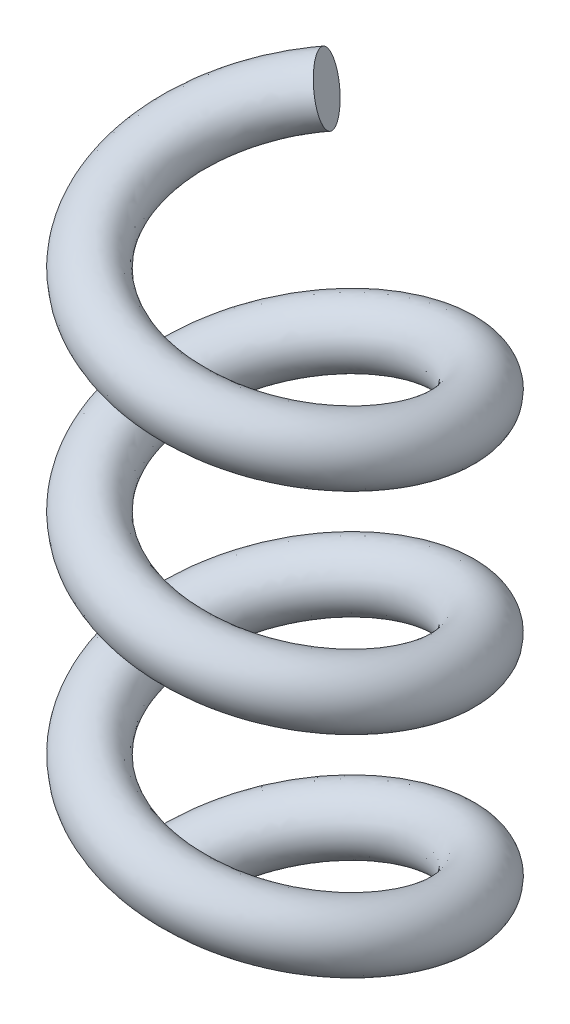
SolidWorks part; units mm, degrees
ref_plane "Front Plane" through (0, 0, 0) normal (0, 0, 1) x (1, 0, 0)
ref_plane "Top Plane" through (0, 0, 0) normal (0, 1, 0) x (1, 0, 0)
ref_plane "Right Plane" through (0, 0, 0) normal (1, 0, 0) x (0, 0, -1)
sketch "Sketch1" plane through (0, 0, 0) normal (0, 1, 0) x (1, 0, 0)
  circle A0 centre (0, 0) radius 25.4
  dimension "D1" = 50.8
curve "Helix/Spiral1" pitch 38.824 height 122.644 turns 3.159
ref_plane "Plane1" through (-13.748, 122.644, -21.3577) normal (0.817, 0.2364, -0.5259) x (-0.5052, -0.1462, -0.8505)
sketch "Sketch2" plane through (-13.748, 122.644, -21.3577) normal (0.817, 0.2364, -0.5259) x (-0.5052, -0.1462, -0.8505)
  circle A0 centre (0.1045, -0.1413) radius 5.5776
  dimension "D1" = 11.1552
sweep "Sweep1" add profiles "Sketch2" path "Helix/Spiral1"
